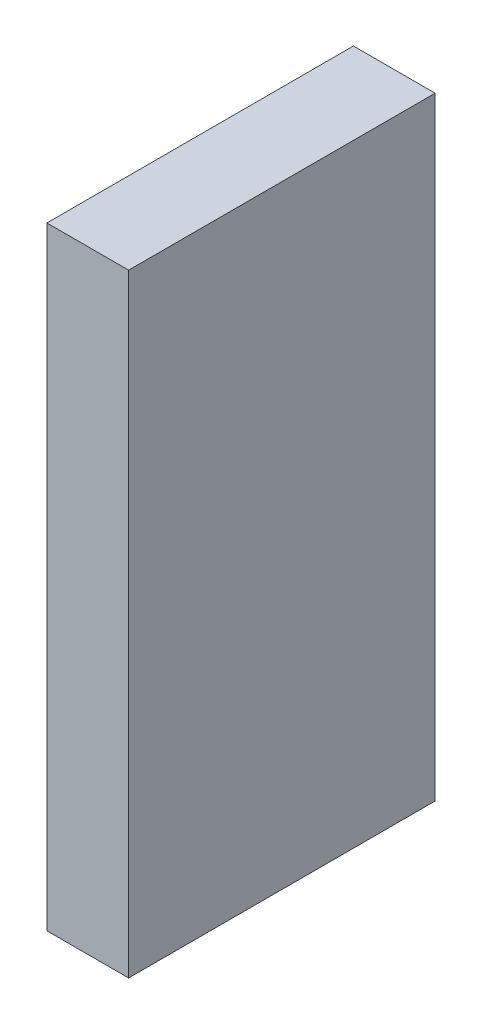
SolidWorks part; units mm, degrees
ref_plane "Спереди" through (0, 0, 0) normal (0, 0, 1) x (1, 0, 0)
ref_plane "Сверху" through (0, 0, 0) normal (0, 1, 0) x (1, 0, 0)
ref_plane "Справа" through (0, 0, 0) normal (1, 0, 0) x (0, 0, -1)
sketch "Эскиз1" plane through (0, 0, 0) normal (1, 0, 0) x (0, 0, -1)
  line L1 (-72.7494, 54.5304) -> (-57.7494, 54.5304)
  line L2 (-72.7494, 54.5304) -> (-72.7494, 24.5304)
  line L3 (-72.7494, 24.5304) -> (-57.7494, 24.5304)
  line L4 (-57.7494, 54.5304) -> (-57.7494, 24.5304)
  dimension "D1" = 15
  dimension "D2" = 30
extrude "Бобышка-Вытянуть1" add sketch "Эскиз1" along normal blind 4
